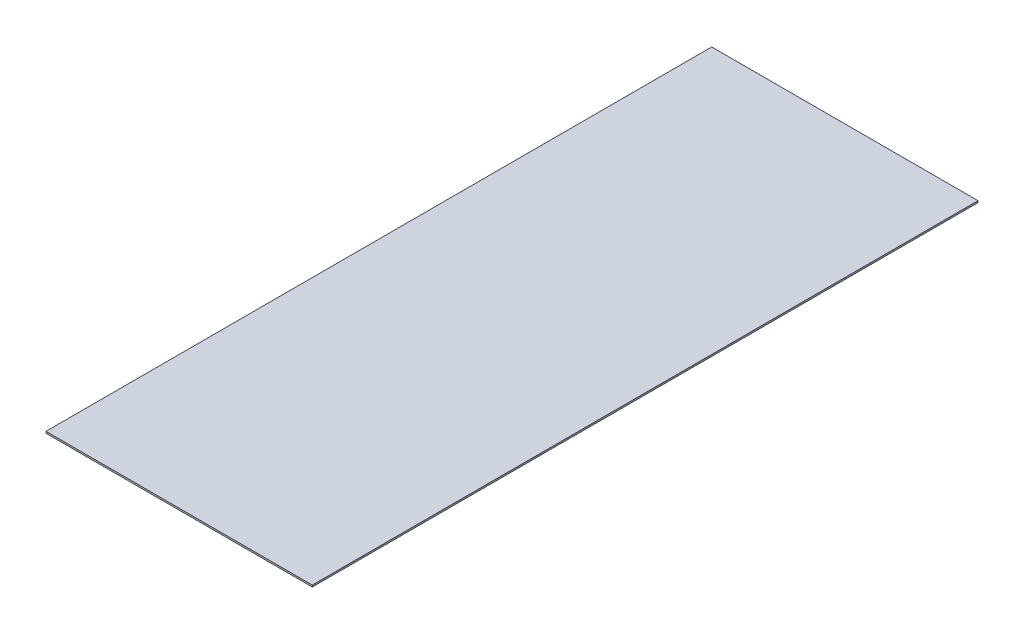
SolidWorks part; units mm, degrees
material "ASTM A36 Acero"
ref_plane "Alzado" through (0, 0, 0) normal (0, 0, 1) x (1, 0, 0)
ref_plane "Planta" through (0, 0, 0) normal (0, 1, 0) x (1, 0, 0)
ref_plane "Vista lateral" through (0, 0, 0) normal (1, 0, 0) x (0, 0, -1)
sketch "Croquis1" plane through (0, 0, 0) normal (0, 1, 0) x (1, 0, 0)
  line L1 (-609.6, -1524) -> (609.6, -1524)
  line L2 (-609.6, -1524) -> (-609.6, 1524)
  line L3 (-609.6, 1524) -> (609.6, 1524)
  line L4 (609.6, -1524) -> (609.6, 1524)
  line L5 (-609.6, -1524) -> (609.6, 1524) construction
  line L6 (-609.6, 1524) -> (609.6, -1524) construction
  point P0 (0, 0)
  dimension "D1" = 3048
  dimension "D2" = 1219.2
extrude "Saliente-Extruir1" add sketch "Croquis1" along normal blind 7.9
